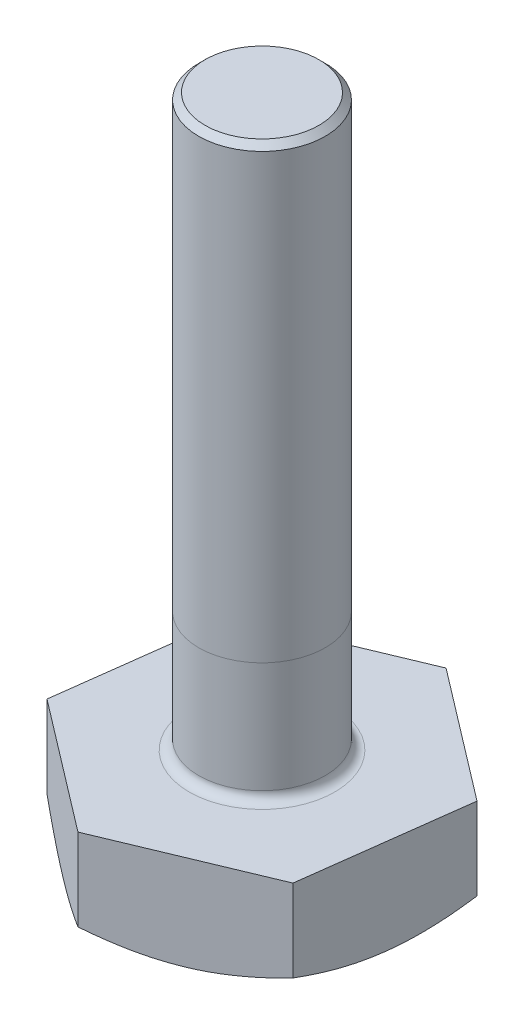
SolidWorks part; units mm, degrees
ref_plane "Front Plane" through (0, 0, 0) normal (0, 0, 1) x (1, 0, 0)
ref_plane "Top Plane" through (0, 0, 0) normal (0, 1, 0) x (1, 0, 0)
ref_plane "Right Plane" through (0, 0, 0) normal (1, 0, 0) x (0, 0, -1)
sketch "Sketch1" plane through (0, 0, 0) normal (0, 1, 0) x (1, 0, 0)
  line L1 (2.0654, -1.5761) -> (2.3976, 1.0007)
  line L2 (2.3976, 1.0007) -> (0.3322, 2.5767)
  line L3 (0.3322, 2.5767) -> (-2.0654, 1.5761)
  line L4 (-2.0654, 1.5761) -> (-2.3976, -1.0007)
  line L5 (-2.3976, -1.0007) -> (-0.3322, -2.5767)
  line L6 (-0.3322, -2.5767) -> (2.0654, -1.5761)
  circle A0 centre (0, 0) radius 2.25 construction
  circle A1 centre (0, 0) radius 1 construction
  point P10 (2.0654, -1.5761)
  point P11 (0, 0)
  dimension "D1" = 2
  dimension "D2" = 4.5
extrude "Boss-Extrude2" add sketch "Sketch1" along normal blind 1.5
sketch "Sketch3" plane through (0, 0, 0) normal (0, 1, 0) x (1, 0, 0)
  circle A0 centre (0, 0) radius 2.25 construction
  circle A1 centre (0, 0) radius 2.25
extrude "Cut-Extrude2" cut sketch "Sketch3" along normal blind 1.5 draft 60 flip side to cut
sketch "Sketch4" plane through (0, 1.5, 0) normal (0, 1, 0) x (1, 0, 0)
  circle A0 centre (0, 0) radius 1 construction
  circle A1 centre (0, 0) radius 1
extrude "Boss-Extrude3" add sketch "Sketch4" along normal blind 9
chamfer "Chamfer1" distance 0.1 angle 45 1 edges at (0, 10.5, 1)
fillet "Fillet1" radius 0.15 1 edges at (0, 1.5, 1)
sketch "Sketch5" plane through (0, 0, 0) normal (0, 0, 1) x (1, 0, 0)
  line L0 (-6.5769, 3.4) -> (6.5769, 3.4)
  line L1 (-1, 10.4) -> (1, 10.4) construction
  point P2 (0, 3.4)
  dimension "D1" = 7
split line "Split Line1"
equation "\"o.1\"=10"
